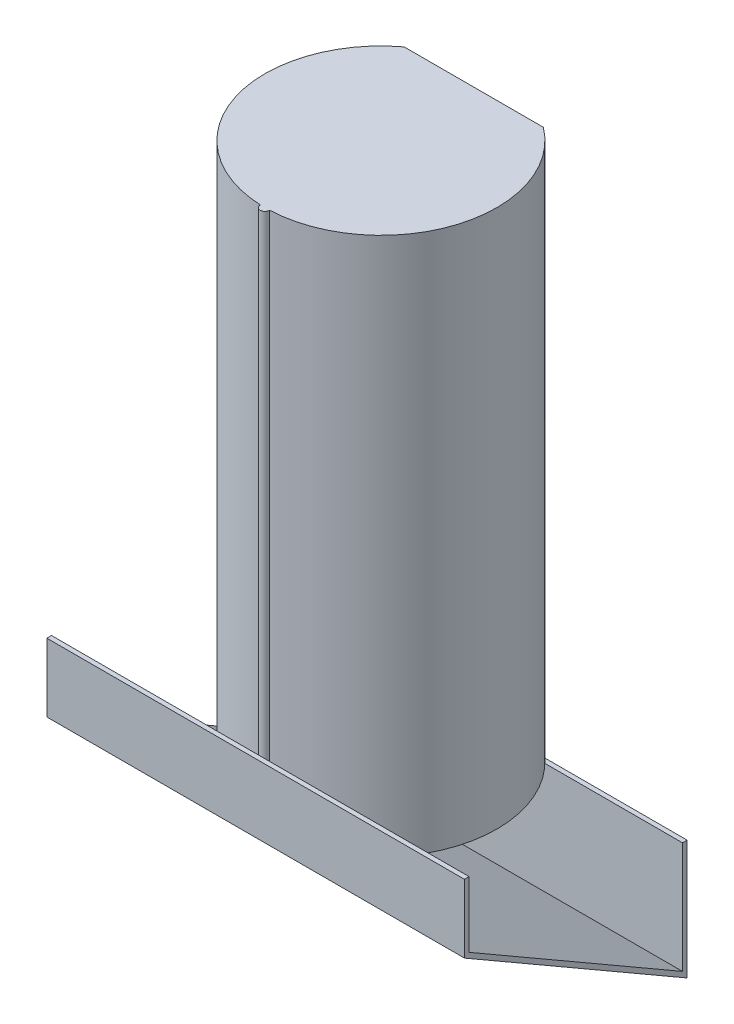
SolidWorks part; units mm, degrees
material "PF"
ref_plane "前视基准面" through (0, 0, 0) normal (0, 0, 1) x (1, 0, 0)
ref_plane "上视基准面" through (0, 0, 0) normal (0, 1, 0) x (1, 0, 0)
ref_plane "右视基准面" through (0, 0, 0) normal (1, 0, 0) x (0, 0, -1)
sketch "草图1" plane through (0, 0, 0) normal (0, 1, 0) x (1, 0, 0)
  line L0 (-7.5, 10) -> (7.5, 10)
  line L1 (0, 21.9994) -> (0, -23.7654) construction
  arc A0 (-7.5, 10) -> (-0.4999, -12.49) centre (0, 0) ccw
  arc A1 (-0.4999, -12.49) -> (0.4999, -12.49) centre (0, -12.5) ccw
  arc A2 (0.4999, -12.49) -> (7.5, 10) centre (0, 0) ccw
  dimension "D1" = 25
  dimension "D3" = 1
  dimension "D2" = 10
extrude "凸台-拉伸1" add sketch "草图1" along normal blind 58
sketch "草图2" plane through (0, 0, 0) normal (1, 0, 0) x (0, 0, -1)
  line L0 (-13, 0) -> (10, -13.2791)
  line L1 (-13, 58) -> (-13, 0) construction
  line L2 (-13, 0) -> (-13, 7.0687)
  line L3 (-13, 7.0687) -> (-13.5, 7.0687)
  line L4 (-13.5, 7.0687) -> (-13.5, -0.2887)
  line L5 (-13.5, -0.2887) -> (10.5, -14.1451)
  line L6 (10, -13.2791) -> (10, -1.2791)
  line L7 (10.5, -14.1451) -> (10.5, -1.2791)
  line L8 (10.5, -1.2791) -> (10, -1.2791)
  point P2 (-13, 0)
  dimension "D1" = 60
  dimension "D2" = 0.5
  dimension "D3" = 0.5
  dimension "D4" = 23.5
  dimension "D5" = 23
  dimension "D6" = 12
extrude "凸台-拉伸2" add sketch "草图2" along normal mid plane 45 separate body
